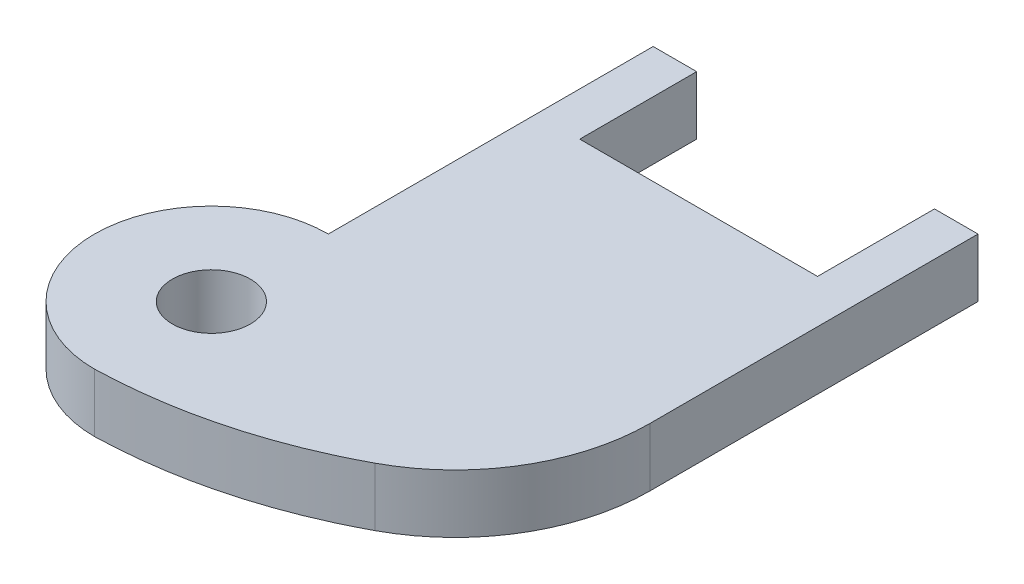
SolidWorks part; units mm, degrees
ref_plane "前视基准面" through (0, 0, 0) normal (0, 0, 1) x (1, 0, 0)
ref_plane "上视基准面" through (0, 0, 0) normal (0, 1, 0) x (1, 0, 0)
ref_plane "右视基准面" through (0, 0, 0) normal (1, 0, 0) x (0, 0, -1)
other "Configuration Table"
sketch "草图1" plane through (0, 0, 0) normal (0, 1, 0) x (1, 0, 0)
  line L0 (0, 0) -> (0, -16.6667)
  line L1 (0, 0) -> (16.6667, 0)
  line L2 (16.6667, 0) -> (16.6667, -22)
  line L3 (0, -16.6667) -> (0, -22.6667) construction
  line L4 (8.3333, 0) -> (8.3333, -9.5254) construction
  line L5 (8.3333, 0) -> (14.4333, 0) construction
  line L6 (14.4333, 0) -> (14.4333, -6)
  line L7 (14.4333, -6) -> (2.2333, -6)
  line L8 (2.2333, 0) -> (2.2333, -6)
  arc A0 (0, -16.6667) -> (0, -28.6667) centre (0, -22.6667) ccw
  circle A1 centre (0, -22.6667) radius 2
  spline S0 degree 2 poles (0, -28.6667) (9.2126, -28.3929) (16.6667, -22) knots 0 0 0 1 1 1
  point P16 (8.3333, -6)
  dimension "D1" = 22
extrude "凸台-拉伸1" add sketch "草图1" along normal blind 3 contours A0 S0 L2 L1 L6 L7 L8 L0 A1
fillet "圆角1" radius 10 1 edges at (16.6667, 1.5, 22)
